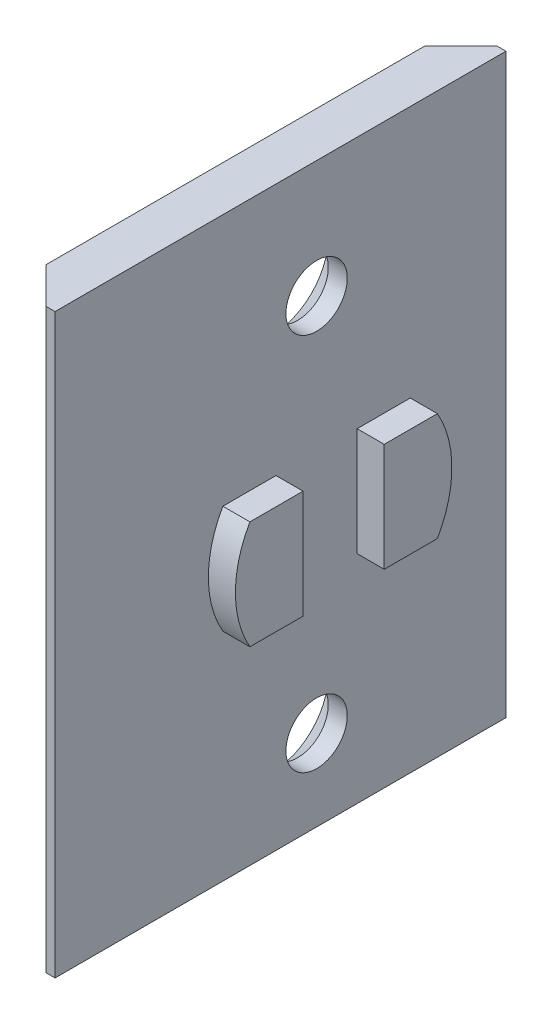
SolidWorks part; units mm, degrees
material "Сталь 10кп ГОСТ 535-88"
ref_plane "Спереди" through (0, 0, 0) normal (0, 0, 1) x (1, 0, 0)
ref_plane "Сверху" through (0, 0, 0) normal (0, 1, 0) x (1, 0, 0)
ref_plane "Справа" through (0, 0, 0) normal (1, 0, 0) x (0, 0, -1)
sketch "Эскиз1" plane through (0, 0, 0) normal (1, 0, 0) x (0, 0, -1)
  line L1 (-12.5, -16) -> (12.5, -16)
  line L2 (-12.5, -16) -> (-12.5, 16)
  line L3 (-12.5, 16) -> (12.5, 16)
  line L4 (12.5, -16) -> (12.5, 16)
  line L5 (-12.5, -16) -> (12.5, 16) construction
  line L6 (-12.5, 16) -> (12.5, -16) construction
  point P0 (0, 0)
  dimension "D1" = 25
  dimension "D2" = 32
extrude "Бобышка-Вытянуть1" add sketch "Эскиз1" along normal blind 2.5
chamfer "Фаска1" distance 2 angle 45 2 edges at (0, 0, 12.5) (0, 0, -12.5)
sketch "Эскиз2" plane through (0, 0, 0) normal (1, 0, 0) x (0, 0, -1)
  point P0 (2, 9.5)
  point P1 (2, -11.5)
hole_wizard "Зенковка для  винта с плоской головкой M31" positions "Трехмерный эскиз1" profile "Эскиз3" countersink size "M3" standard "Ansi Metric" end condition through all
sketch3d "Трехмерный эскиз1"
  point P0 (0, -11.5, -2)
  point P3 (0, 9.5, -2)
sketch "Эскиз3" plane through (0, -11.5, -2) normal (0, 1, 0) x (0, 0, 1)
  line L0 (0, 0) -> (0, 2.5)
  line L1 (0, 2.5) -> (1.7, 2.5)
  line L2 (1.7, 2.5) -> (1.7, 1.45)
  line L3 (1.7, 1.45) -> (3.15, 0)
  line L5 (3.15, 0) -> (0, 0)
  line L6 (-1.7, 1.45) -> (-3.15, 0) construction
  line L11 (0, -6.35) -> (0, 107.95) construction
  dimension "Диаметр сквозного отверстия" = 3.4
  dimension "Глубина сквозного отверстия" = 2.5
  dimension "Диаметр передней зенковки" = 6.3
  dimension "Угол передней зенковки" = 90
sketch "Эскиз4" plane through (2.5, 0, 0) normal (1, 0, 0) x (0, 0, -1)
  line L1 (-0.25, -3.7) -> (4.25, -3.7)
  line L2 (-0.25, -3.7) -> (-0.25, 1.7)
  line L3 (-0.25, 1.7) -> (4.25, 1.7)
  line L4 (4.25, -3.7) -> (4.25, 1.7)
  line L5 (-0.25, -3.7) -> (4.25, 1.7) construction
  line L6 (-0.25, 1.7) -> (4.25, -3.7) construction
  circle A0 centre (2, -1) radius 6
  circle A1 centre (2, -1) radius 3.5
  dimension "D1" = 12
  dimension "D2" = 7
  dimension "D3" = 5.4
  dimension "D4" = 4.5
extrude "Бобышка-Вытянуть2" add sketch "Эскиз4" along normal blind 1.5 contours A0 A1 | L2 A1 | L4 A1
sketch "Эскиз5" plane through (4, 0, 0) normal (1, 0, 0) x (0, 0, -1)
  line L0 (4.25, -3.7) -> (4.25, 1.7) construction
  line L1 (-0.25, -9) -> (4.25, -9)
  line L2 (-0.25, -9) -> (-0.25, 7)
  line L3 (-0.25, 7) -> (4.25, 7)
  line L4 (4.25, -9) -> (4.25, 7)
  line L5 (-0.25, -9) -> (4.25, 7) construction
  line L6 (-0.25, 7) -> (4.25, -9) construction
  point P0 (2, -1)
  dimension "D1" = 16
extrude "Вырез-Вытянуть1" cut sketch "Эскиз5" against normal up to surface (1.5 mm away) up to face at (2.5, -1, 4)
sketch "Эскиз6" plane through (4, 0, 0) normal (1, 0, 0) x (0, 0, -1)
  line L1 (-3.1962, -4) -> (7.1962, -4)
  line L2 (-3.1962, -4) -> (-3.1962, 2)
  line L3 (-3.1962, 2) -> (7.1962, 2)
  line L4 (7.1962, -4) -> (7.1962, 2)
  line L5 (-3.1962, -4) -> (7.1962, 2) construction
  line L6 (-3.1962, 2) -> (7.1962, -4) construction
  circle A0 centre (2, -1) radius 6
  arc A2 (4.25, -6.5621) -> (4.25, 4.5621) centre (2, -1) ccw construction
  line M1 (4.25, 4.5621) -> (4.25, -6.5621)
  arc M2 (4.25, -6.5621) -> (4.25, 4.5621) centre (2, -1) ccw
  dimension "D1" = 6
extrude "Вырез-Вытянуть2" cut sketch "Эскиз6" against normal up to surface (1.5 mm away) contours A0 L3 M1 | L3 M1 M2 | L1 A0 M1 | L1 M1 M2 up to face at (2.5, -1, 2.125)
